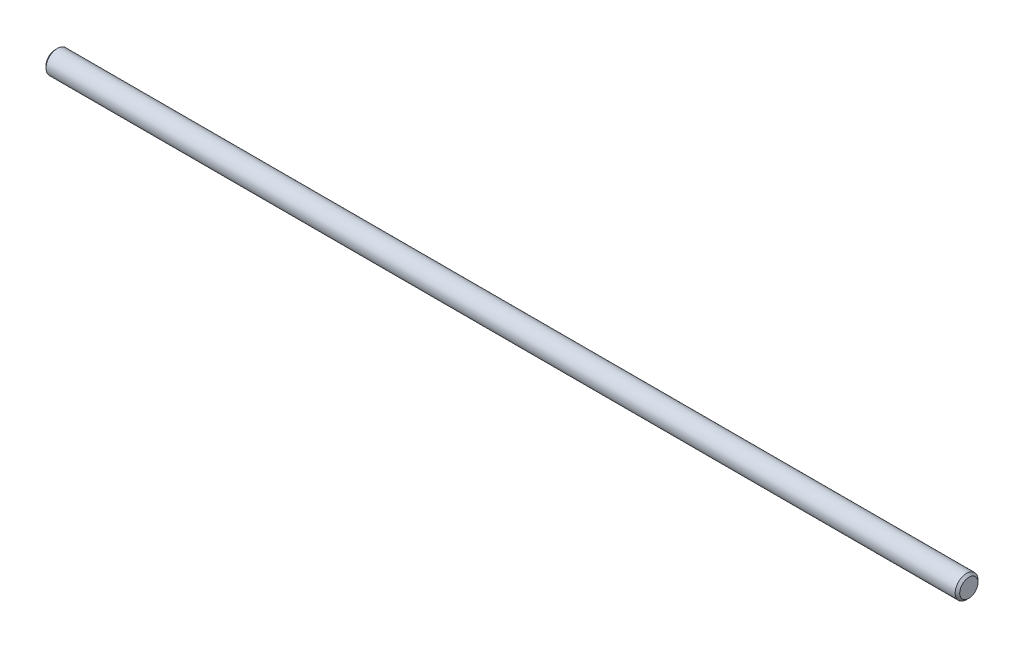
SolidWorks part; units mm, degrees
ref_plane "Front" through (0, 0, 0) normal (0, 0, 1) x (1, 0, 0)
ref_plane "Top" through (0, 0, 0) normal (0, 1, 0) x (1, 0, 0)
ref_plane "Right" through (0, 0, 0) normal (1, 0, 0) x (0, 0, -1)
sketch "Sketch1" plane through (0, 0, 0) normal (0, 0, 1) x (1, 0, 0)
  line L0 (-127, 0) -> (127, 0) construction
  line L1 (127, 3.175) -> (127, -3.175) construction
  line L2 (-127, 3.175) -> (-127, -3.175) construction
  dimension "Length" = 254
  dimension "Diameter" = 6.35
sketch "Sketch2" plane through (0, 0, 0) normal (1, 0, 0) x (0, 0, -1)
  circle A0 centre (0, 0) radius 3.175
extrude "Extrude1" add sketch "Sketch2" against normal up to vertex (127 mm away) and the other way up to vertex (127 mm away) up to point (-127, 3.175, 0) other way up to point (127, 3.175, 0)
chamfer "Chamfer1" distance 0.635 angle 45 2 edges at (127, 0, -3.175) (-127, 0, -3.175)
equation "\"D1@Chamfer1\" = \"Diameter@Sketch1\"*.1"
